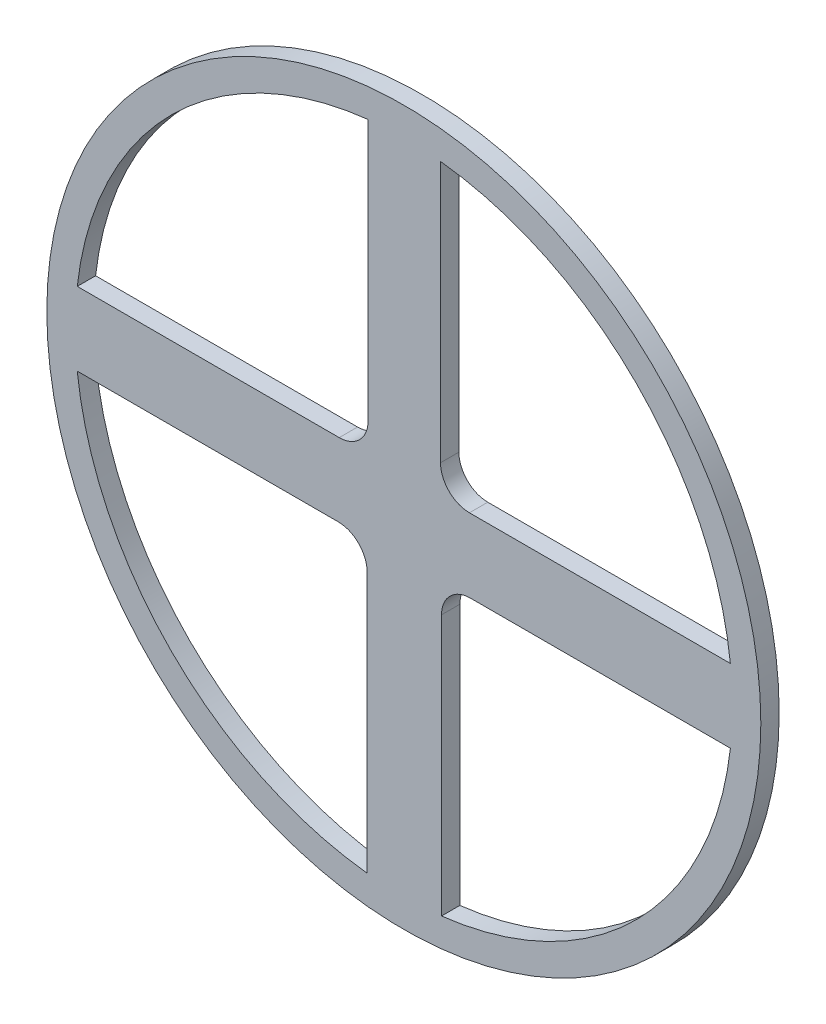
SolidWorks part; units mm, degrees
ref_plane "Front Plane" through (0, 0, 0) normal (0, 0, 1) x (1, 0, 0)
ref_plane "Top Plane" through (0, 0, 0) normal (0, 1, 0) x (1, 0, 0)
ref_plane "Right Plane" through (0, 0, 0) normal (1, 0, 0) x (0, 0, -1)
sketch "Sketch1" plane through (0, 0, 0) normal (0, 0, 1) x (1, 0, 0)
  line L0 (0, -113.71) -> (0, 113.71) construction
  line L2 (12.7, 22.7) -> (12.7, 116.188)
  line L4 (-12.3556, 22.7) -> (-12.3556, 113.0367)
  line L5 (13.0444, -119.3392) -> (-12.3556, 113.0367) construction
  line L6 (12.7, 116.188) -> (-12.7, -116.188) construction
  line L7 (-116.188, -12.7) -> (-22.7, -12.7)
  line L9 (-116.188, 12.7) -> (-22.3556, 12.7)
  line L11 (-116.188, -12.7) -> (116.188, 12.7) construction
  line L12 (-116.188, 12.7) -> (116.188, -12.7) construction
  line L13 (-113.71, 0) -> (113.71, 0) construction
  line L14 (22.7, 12.7) -> (116.188, 12.7)
  line L15 (13.0444, -22.7) -> (13.0444, -119.3392)
  line L16 (-12.7, -22.7) -> (-12.7, -116.188)
  line L17 (23.0444, -12.7) -> (116.188, -12.7)
  circle A0 centre (0, 0) radius 123.5325
  circle A1 centre (0, 0) radius 113.71
  arc A2 (-12.3556, 22.7) -> (-22.3556, 12.7) centre (-22.3556, 22.7) cw
  arc A3 (22.7, 12.7) -> (12.7, 22.7) centre (22.7, 22.7) cw
  arc A4 (-12.7, -22.7) -> (-22.7, -12.7) centre (-22.7, -22.7) ccw
  arc A5 (13.0444, -22.7) -> (23.0444, -12.7) centre (23.0444, -22.7) cw
  point P28 (13.0444, -12.7)
  dimension "D1" = 247.065
  dimension "D2" = 227.42
  dimension "D5" = 10
  dimension "D6" = 10
  dimension "D7" = 10
  dimension "D8" = 10
  dimension "D3" = 12.7
  dimension "D4" = 12.7
extrude "Boss-Extrude1" add sketch "Sketch1" along normal blind 6.35 contours A0 A1 | L15 A5 L17 A1 L14 A3 L2 L4 A2 L9 L7 A4 L16
